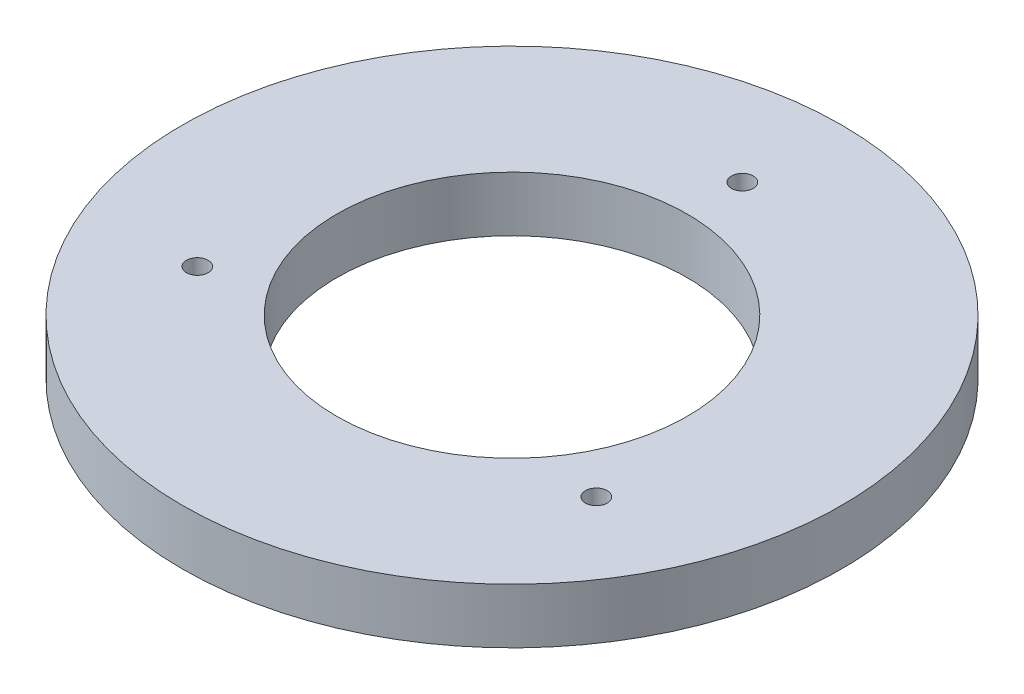
SolidWorks part; units mm, degrees
ref_plane "Front Plane" through (0, 0, 0) normal (0, 0, 1) x (1, 0, 0)
ref_plane "Top Plane" through (0, 0, 0) normal (0, 1, 0) x (1, 0, 0)
ref_plane "Right Plane" through (0, 0, 0) normal (1, 0, 0) x (0, 0, -1)
sketch "Sketch2" plane through (0, 0, 0) normal (0, 1, 0) x (1, 0, 0)
  circle A0 centre (0, 0) radius 37.973
  circle A1 centre (0, 0) radius 20.193
  dimension "D1" = 75.946
  dimension "D2" = 40.386
extrude "Boss-Extrude1" add sketch "Sketch2" along normal mid plane 6.35
sketch "Sketch3" plane through (0, 3.175, 0) normal (0, 1, 0) x (1, 0, 0)
  line L1 (0, 26.5431) -> (-22.987, -13.2716)
  line L2 (-22.987, -13.2716) -> (22.987, -13.2716)
  line L3 (22.987, -13.2716) -> (0, 26.5431)
  circle A0 centre (0, 0) radius 13.2716 construction
  dimension "D1" = 45.974
sketch "Sketch4" plane through (0, 3.175, 0) normal (0, 1, 0) x (1, 0, 0)
  circle A0 centre (-22.987, -13.2716) radius 1.25
  circle A1 centre (0, 26.5431) radius 1.25
  circle A2 centre (22.987, -13.2716) radius 1.25
  dimension "D1" = 2.5
  dimension "D2" = 2.5
  dimension "D3" = 2.5
extrude "Cut-Extrude1" cut sketch "Sketch4" against normal through all
